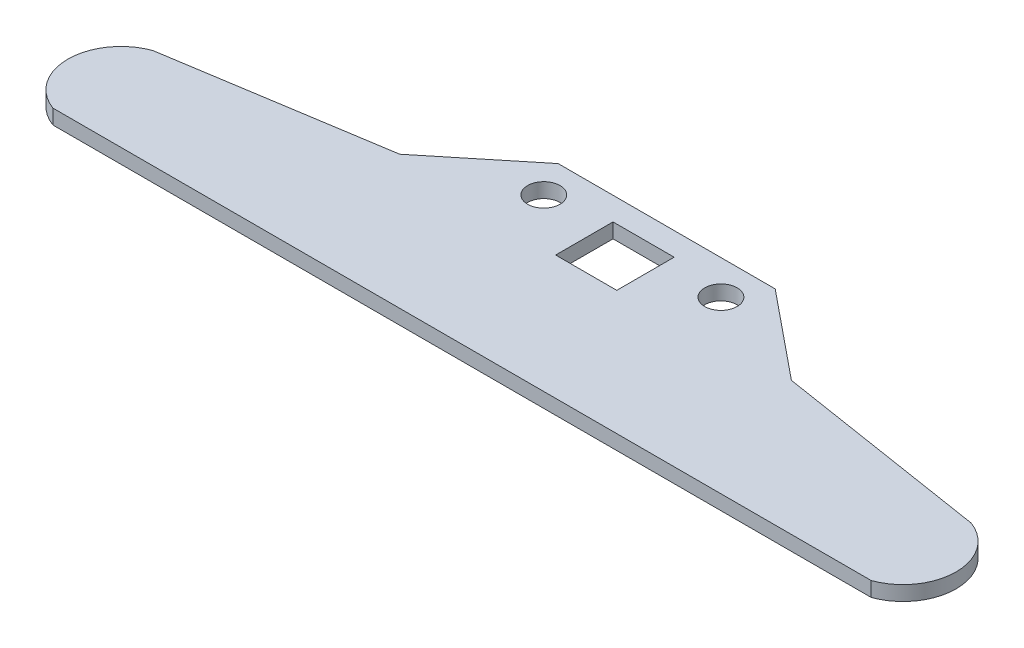
SolidWorks part; units mm, degrees
ref_plane "Front Plane" through (0, 0, 0) normal (0, 0, 1) x (1, 0, 0)
ref_plane "Top Plane" through (0, 0, 0) normal (0, 1, 0) x (1, 0, 0)
ref_plane "Right Plane" through (0, 0, 0) normal (1, 0, 0) x (0, 0, -1)
sketch "Sketch1" plane through (0, 0, 0) normal (0, 1, 0) x (1, 0, 0)
  line L0 (0, -1000) -> (0, 49000) construction
  line L1 (70.7804, 0) -> (-70.7804, 0)
  line L2 (-70.7804, 17.2635) -> (-33.8796, 23.0899)
  line L3 (-33.8796, 23.0899) -> (-18.7741, 35.3902)
  line L4 (-18.7741, 35.3902) -> (18.7741, 35.3902)
  line L5 (33.8796, 23.0899) -> (18.7741, 35.3902)
  line L6 (70.7804, 17.2635) -> (33.8796, 23.0899)
  line L7 (-55, 0) -> (55, 0) construction
  line L8 (0, -55) -> (0, 55) construction
  line L9 (-5.287, 31.398) -> (5.287, 31.398)
  line L10 (-5.287, 31.398) -> (-5.287, 21.4715)
  line L11 (-5.287, 21.4715) -> (5.287, 21.4715)
  line L12 (5.287, 31.398) -> (5.287, 21.4715)
  arc A0 (-70.7804, 0) -> (-70.7804, 17.2635) centre (-67.6514, 8.6318) cw
  arc A1 (70.7804, 0) -> (70.7804, 17.2635) centre (67.6514, 8.6318) ccw
  circle A2 centre (-15.3214, 29.4559) radius 2.8053
  circle A3 centre (15.3214, 29.4559) radius 2.8053
  point P14 (0, 35.3902)
  point P15 (0, 0)
  point P21 (0, 31.398)
extrude "Boss-Extrude1" add sketch "Sketch1" along normal blind 2.54
